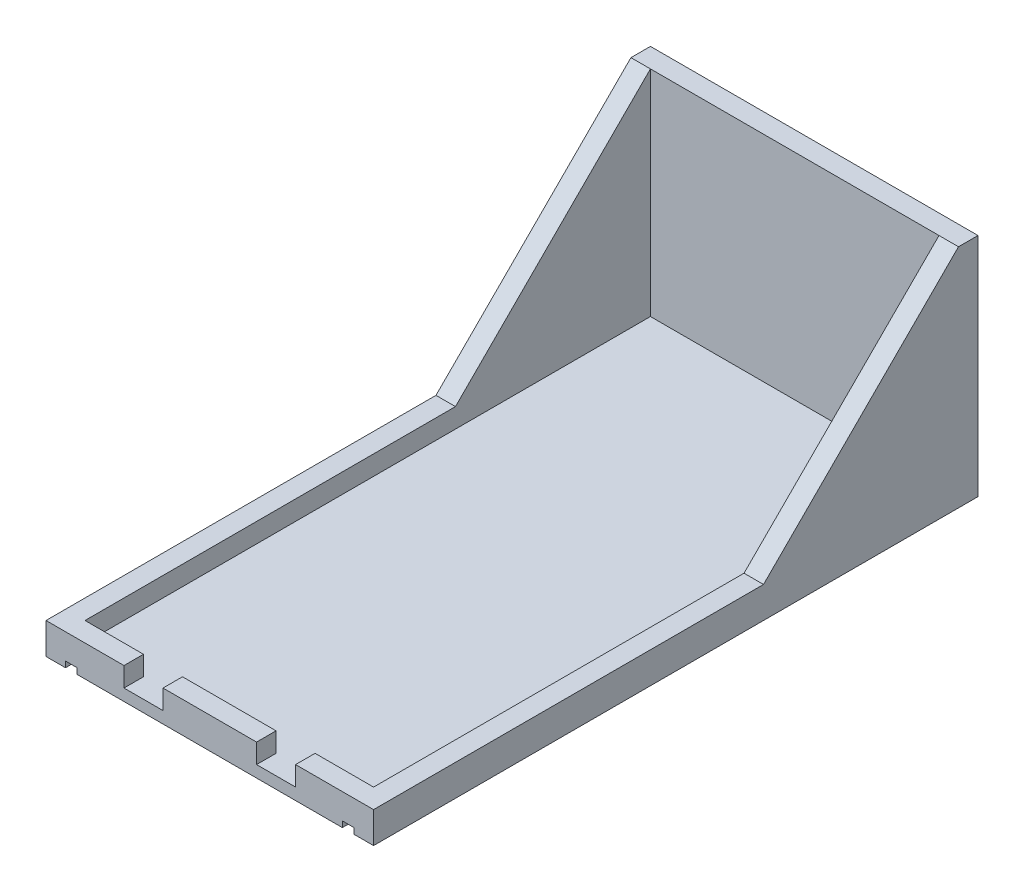
SolidWorks part; units mm, degrees
ref_plane "Front Plane" through (0, 0, 0) normal (0, 0, 1) x (1, 0, 0)
ref_plane "Top Plane" through (0, 0, 0) normal (0, 1, 0) x (1, 0, 0)
ref_plane "Right Plane" through (0, 0, 0) normal (1, 0, 0) x (0, 0, -1)
sketch "Sketch1" plane through (0, 0, 0) normal (0, 1, 0) x (1, 0, 0)
  line L1 (42, -77.5) -> (-42, -77.5)
  line L2 (42, -77.5) -> (42, 77.5)
  line L3 (42, 77.5) -> (-42, 77.5)
  line L4 (-42, -77.5) -> (-42, 77.5)
  line L5 (42, -77.5) -> (-42, 77.5) construction
  line L6 (42, 77.5) -> (-42, -77.5) construction
  point P0 (0, 0)
  dimension "D1" = 84
  dimension "D2" = 155
extrude "Boss-Extrude1" add sketch "Sketch1" along normal blind 3
sketch "Sketch2" plane through (0, 3, 0) normal (0, 1, 0) x (1, 0, 0)
  line L0 (42, -77.5) -> (42, 77.5) construction
  line L1 (37, -72.5) -> (34, -72.5)
  line L2 (37, -72.5) -> (37, -69.5)
  line L3 (37, -69.5) -> (34, -69.5)
  line L4 (34, -72.5) -> (34, -69.5)
  line L5 (-42, -77.5) -> (42, -77.5) construction
  line L6 (-42, 77.5) -> (-42, -77.5) construction
  line L7 (-37, -69.5) -> (-34, -69.5)
  line L8 (-37, -69.5) -> (-37, -72.5)
  line L9 (-37, -72.5) -> (-34, -72.5)
  line L10 (-34, -69.5) -> (-34, -72.5)
  dimension "D1" = 5
  dimension "D2" = 5
  dimension "D3" = 3
  dimension "D4" = 3
  dimension "D5" = 5
  dimension "D6" = 5
  dimension "D7" = 3
  dimension "D8" = 3
extrude "Cut-Extrude1" cut sketch "Sketch2" against normal blind 3
sketch "Sketch3" plane through (0, 0, 77.5) normal (0, 0, 1) x (1, 0, 0)
  line L0 (-42, 3) -> (42, 3) construction
  line L1 (42, 0) -> (37, 0)
  line L2 (42, 0) -> (42, 8)
  line L3 (42, 8) -> (37, 8)
  line L4 (37, 0) -> (37, 8)
  dimension "D1" = 5
  dimension "D2" = 5
extrude "Boss-Extrude2" add sketch "Sketch3" against normal blind 155
sketch "Sketch4" plane through (0, 0, 77.5) normal (0, 0, 1) x (1, 0, 0)
  line L0 (-42, 3) -> (37, 3) construction
  line L1 (-42, 0) -> (-37, 0)
  line L2 (-42, 0) -> (-42, 8)
  line L3 (-42, 8) -> (-37, 8)
  line L4 (-37, 0) -> (-37, 8)
  dimension "D1" = 5
  dimension "D2" = 5
extrude "Boss-Extrude3" add sketch "Sketch4" against normal blind 155
sketch "Sketch5" plane through (-42, 0, 0) normal (-1, 0, 0) x (0, 0, 1)
  line L0 (-77.5, 8) -> (77.5, 8) construction
  line L1 (-77.5, 0) -> (-72.5, 0)
  line L2 (-77.5, 0) -> (-77.5, 58)
  line L3 (-77.5, 58) -> (-72.5, 58)
  line L4 (-72.5, 0) -> (-72.5, 58)
  dimension "D1" = 5
  dimension "D2" = 50
extrude "Boss-Extrude4" add sketch "Sketch5" against normal blind 84
sketch "Sketch6" plane through (-42, 0, 0) normal (-1, 0, 0) x (0, 0, 1)
  line L0 (-72.5, 58) -> (-22.5, 8)
  line L1 (-72.5, 8) -> (77.5, 8) construction
  line L2 (-22.5, 8) -> (-74.3, 4.4168)
  line L3 (-74.3, 4.4168) -> (-74.3, 56.2)
  line L4 (-74.3, 56.2) -> (-72.5, 58)
extrude "Boss-Extrude5" add sketch "Sketch6" against normal blind 5
sketch "Sketch7" plane through (42, 0, 0) normal (1, 0, 0) x (0, 0, -1)
  line L0 (72.5, 58) -> (19.1089, 4.6089)
  line L1 (19.1089, 4.6089) -> (75.2476, 4.6089)
  line L2 (75.2476, 4.6089) -> (75.2476, 53.9164)
  line L3 (75.2476, 53.9164) -> (72.5, 58)
extrude "Boss-Extrude6" add sketch "Sketch7" against normal blind 5
sketch "Sketch8" plane through (0, 0, 77.5) normal (0, 0, 1) x (1, 0, 0)
  line L1 (42, 0) -> (-42, 0)
  line L2 (42, 0) -> (42, 8)
  line L3 (42, 8) -> (-42, 8)
  line L4 (-42, 0) -> (-42, 8)
extrude "Boss-Extrude8" add sketch "Sketch8" against normal blind 5
sketch "Sketch10" plane through (0, 0, 77.5) normal (0, 0, 1) x (1, 0, 0)
  line L0 (-42, 0) -> (42, 0) construction
  line L1 (-22, 3) -> (-12, 3)
  line L2 (-22, 3) -> (-22, 10.4972)
  line L3 (-22, 10.4972) -> (-12, 10.4972)
  line L4 (-12, 3) -> (-12, 10.4972)
  line L5 (-42, 8) -> (-42, 0) construction
  dimension "D1" = 3
  dimension "D2" = 20
  dimension "D3" = 10
extrude "Cut-Extrude2" cut sketch "Sketch10" against normal blind 5
sketch "Sketch11" plane through (0, 0, 77.5) normal (0, 0, 1) x (1, 0, 0)
  line L0 (42, 8) -> (42, 0) construction
  line L1 (22, 3) -> (12, 3)
  line L2 (22, 3) -> (22, 13.6666)
  line L3 (22, 13.6666) -> (12, 13.6666)
  line L4 (12, 3) -> (12, 13.6666)
  line L5 (-42, 0) -> (42, 0) construction
  dimension "D1" = 10
  dimension "D2" = 20
  dimension "D3" = 3
extrude "Cut-Extrude3" cut sketch "Sketch11" against normal blind 5
sketch "Sketch12" plane through (0, 0, 0) normal (0, -1, 0) x (-1, 0, 0)
  line L0 (42, -77.5) -> (-42, -77.5) construction
  line L1 (37, -72.5) -> (34.0087, -72.5)
  line L2 (37, -72.5) -> (37, -77.5)
  line L3 (37, -77.5) -> (34.0087, -77.5)
  line L4 (34.0087, -72.5) -> (34.0087, -77.5)
extrude "Cut-Extrude4" cut sketch "Sketch12" against normal blind 1.5
sketch "Sketch13" plane through (0, 0, 0) normal (0, -1, 0) x (-1, 0, 0)
  line L0 (-34, -72.5) -> (-34, -80.1939)
  line L1 (-37, -72.5) -> (-37, -80.0754)
  line L2 (-37, -80.0754) -> (-34, -80.1939)
  line L3 (-34, -72.5) -> (-37, -72.5)
extrude "Cut-Extrude5" cut sketch "Sketch13" against normal blind 1.5
